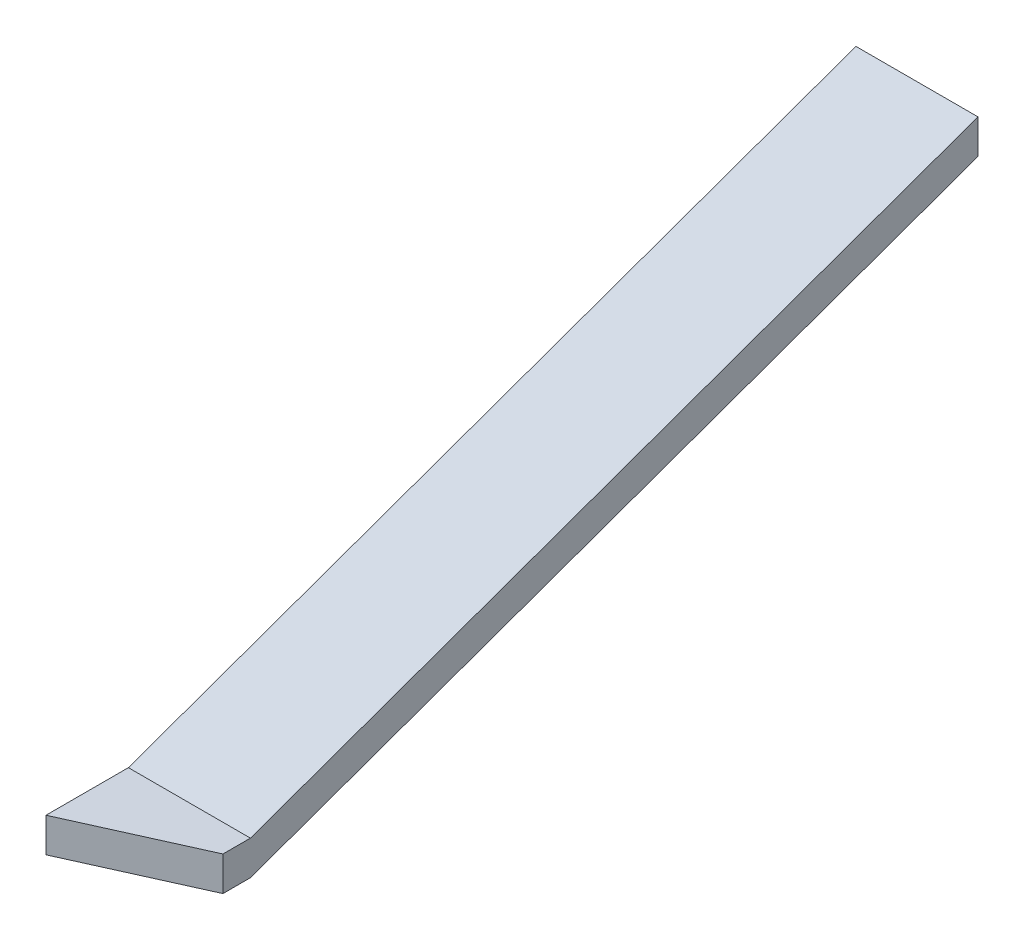
SolidWorks part; units mm, degrees
ref_plane "Alzado" through (0, 0, 0) normal (0, 0, 1) x (1, 0, 0)
ref_plane "Planta" through (0, 0, 0) normal (0, 1, 0) x (1, 0, 0)
ref_plane "Vista lateral" through (0, 0, 0) normal (1, 0, 0) x (0, 0, -1)
sketch "Croquis1" plane through (0, 0, 0) normal (0, 0, 1) x (1, 0, 0)
  line L1 (0, 0) -> (88.9, 0)
  line L2 (0, 0) -> (0, 25)
  line L3 (0, 25) -> (88.9, 25)
  line L4 (88.9, 0) -> (88.9, 25)
  dimension "D1" = 25
  dimension "D2" = 88.9
extrude "Saliente-Extruir1" add sketch "Croquis1" against normal blind 60
sketch3d "Croquis3D1"
  line L0 (44.45, 25, -60) -> (44.45, 0, -60) construction
  line L1 (88.9, 25, -60) -> (0, 25, -60) construction
  line L2 (0, 0, -60) -> (88.9, 0, -60) construction
  line L3 (44.45, 12.5, -60) -> (44.45, 12.5, -590) construction
  line L4 (44.45, 12.5, -590) -> (44.45, 202.5, -590) construction
  line L5 (44.45, 202.5, -590) -> (44.45, 12.5, -60)
  dimension "D1" = 530
  dimension "D2" = 190
sketch "Croquis2" plane through (0, 0, -60) normal (0, 0, -1) x (-1, 0, 0)
  line L1 (-88.9, 25) -> (0, 25)
  line L2 (-88.9, 25) -> (-88.9, 0)
  line L3 (-88.9, 0) -> (0, 0)
  line L4 (0, 25) -> (0, 0)
sweep "Barrer1" add profiles "Croquis2" path "Croquis3D1"
sketch "Croquis3" plane through (0, 25, 0) normal (0, 1, 0) x (1, 0, 0)
  line L0 (0, 0) -> (88.9, 40)
  line L1 (88.9, 60) -> (88.9, 0) construction
  line L2 (88.9, 40) -> (88.9, 0)
  line L3 (88.9, 0) -> (0, 0)
  dimension "D1" = 40
extrude "Cortar-Extruir1" cut sketch "Croquis3" against normal blind 100
